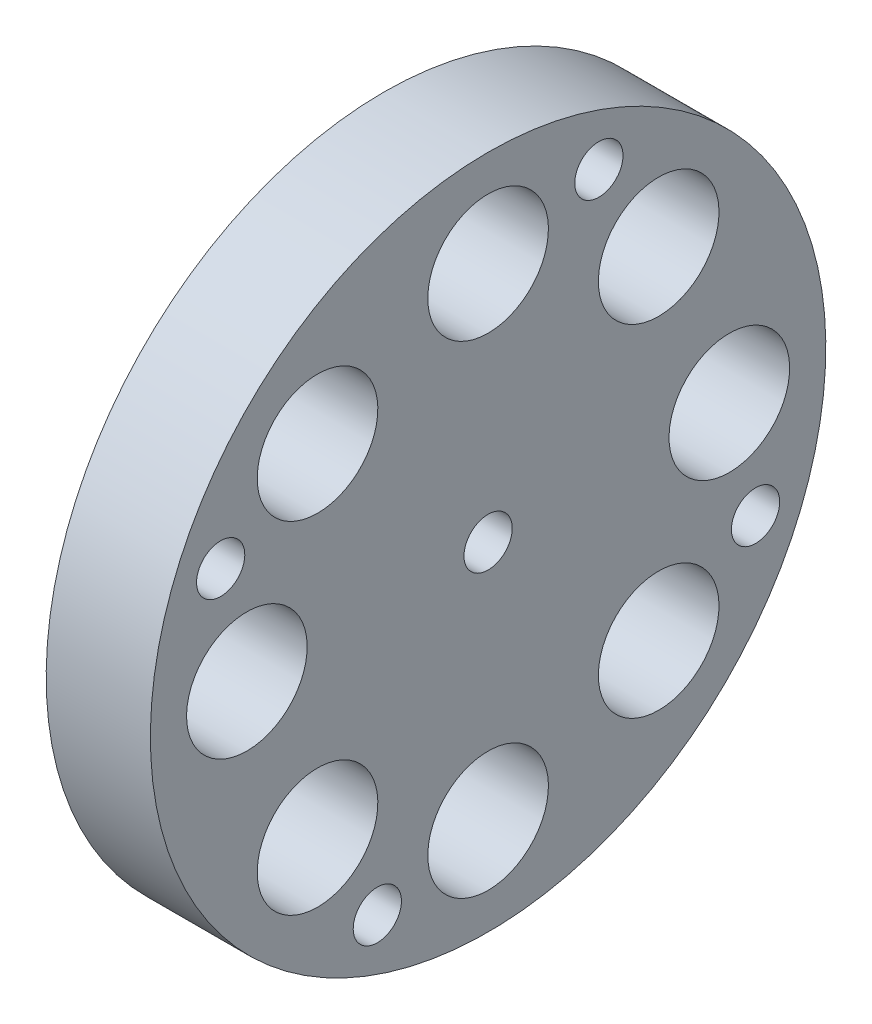
SolidWorks part; units mm, degrees
material "PE High Density Film"
ref_plane "Front Plane" through (0, 0, 0) normal (0, 0, 1) x (1, 0, 0)
ref_plane "Top Plane" through (0, 0, 0) normal (0, 1, 0) x (1, 0, 0)
ref_plane "Right Plane" through (0, 0, 0) normal (1, 0, 0) x (0, 0, -1)
sketch "Sketch1" plane through (0, 0, 0) normal (0, 0, 1) x (1, 0, 0)
  line L0 (0, 0) -> (-14.478, 0) construction
  line L1 (0, 0) -> (0, 22.225)
  line L2 (0, 22.225) -> (-6.858, 22.225)
  line L3 (-6.858, 22.225) -> (-6.858, 6.35)
  line L4 (-6.858, 6.35) -> (-14.478, 6.35)
  line L5 (-14.478, 6.35) -> (-14.478, 0)
  line L6 (0, 0) -> (-14.478, 0)
  dimension "D1" = 44.45
  dimension "D2" = 6.858
  dimension "D3" = 7.62
  dimension "D4" = 12.7
revolve "Revolve1" add sketch "Sketch1" angle 360 about L0
sketch "Sketch2" plane through (-6.858, 0, 0) normal (-1, 0, 0) x (0, 0, 1)
  line L0 (0, 0) -> (0, 15.875) construction
  circle A0 centre (0, 0) radius 15.875 construction
  circle A1 centre (0, 15.875) radius 3.9688
  circle A2 centre (11.2253, 11.2253) radius 3.9687
  circle A3 centre (15.875, 0) radius 3.9688
  circle A4 centre (11.2253, -11.2253) radius 3.9688
  circle A5 centre (0, -15.875) radius 3.9688
  circle A6 centre (-11.2253, -11.2253) radius 3.9688
  circle A7 centre (-15.875, 0) radius 3.9688
  circle A8 centre (-11.2253, 11.2253) radius 3.9688
  point P22 (0, 0)
  dimension "D1" = 8
  dimension "D2" = 7.9375
  dimension "D3" = 31.75
extrude "Cut-Extrude1" cut sketch "Sketch2" against normal through all
sketch "Sketch4" plane through (-14.478, 0, 0) normal (-1, 0, 0) x (0, 0, 1)
  circle A0 centre (0, 0) radius 2.5
  dimension "D1" = 5
extrude "Cut-Extrude2" cut sketch "Sketch4" against normal offset from surface (9.7155 mm away) 4.7625 up to face at (0, 7.2566, -11.2253)
chamfer "Chamfer1" [suppressed] distance 0.635 angle 45
sketch "Sketch5" plane through (0, 0, 0) normal (1, 0, 0) x (0, 0, -1)
  line L0 (-11.2253, 11.2253) -> (0, 0) construction
  line L1 (-15.875, 0) -> (0, 0) construction
  line L2 (0, 0) -> (-17.5999, 7.2901) construction
  circle A0 centre (0, 0) radius 1.5875
  circle A1 centre (0, 0) radius 9.6266 construction
  circle A2 centre (0, 0) radius 19.05 construction
  circle A3 centre (-17.5999, 7.2901) radius 1.5875
  circle A4 centre (7.2901, 17.5999) radius 1.5875
  circle A5 centre (17.5999, -7.2901) radius 1.5875
  circle A6 centre (-7.2901, -17.5999) radius 1.5875
  point P20 (0, 0)
  dimension "D1" = 3.175
  dimension "D2" = 38.1
  dimension "D3" = 3.175
  dimension "D4" = 4
extrude "Cut-Extrude3" cut sketch "Sketch5" against normal blind 2.3813
hole_wizard "#4-40 Tapped Hole1" positions "Sketch7" profile "Sketch6" tap size "#4-40" standard "ANSI Inch"
sketch "Sketch7" plane through (0, 0, 0) normal (0, 0, 1) x (1, 0, 0)
  line L0 (0, 0) -> (-19.7218, 0) construction
  line L1 (-10.668, -6.35) -> (-10.668, 6.35) construction
  line L2 (-14.478, -6.35) -> (-6.858, -6.35) construction
  line L3 (-6.858, 6.35) -> (-14.478, 6.35) construction
  point P0 (-10.668, 0)
sketch "Sketch6" plane through (-10.668, 0, 0) normal (1, 0, 0) x (0, 1, 0)
  line L0 (0, 0) -> (0, 22.225)
  line L1 (0, 22.225) -> (1.1303, 22.225)
  line L2 (1.1303, 22.225) -> (1.1303, 0)
  line L5 (1.1303, 0) -> (0, 0)
  line L11 (0, -6.35) -> (0, 107.95) construction
  dimension "Thread Major Dia." = 2.2606
  dimension "Thru Tap Drill Depth" = 22.225
